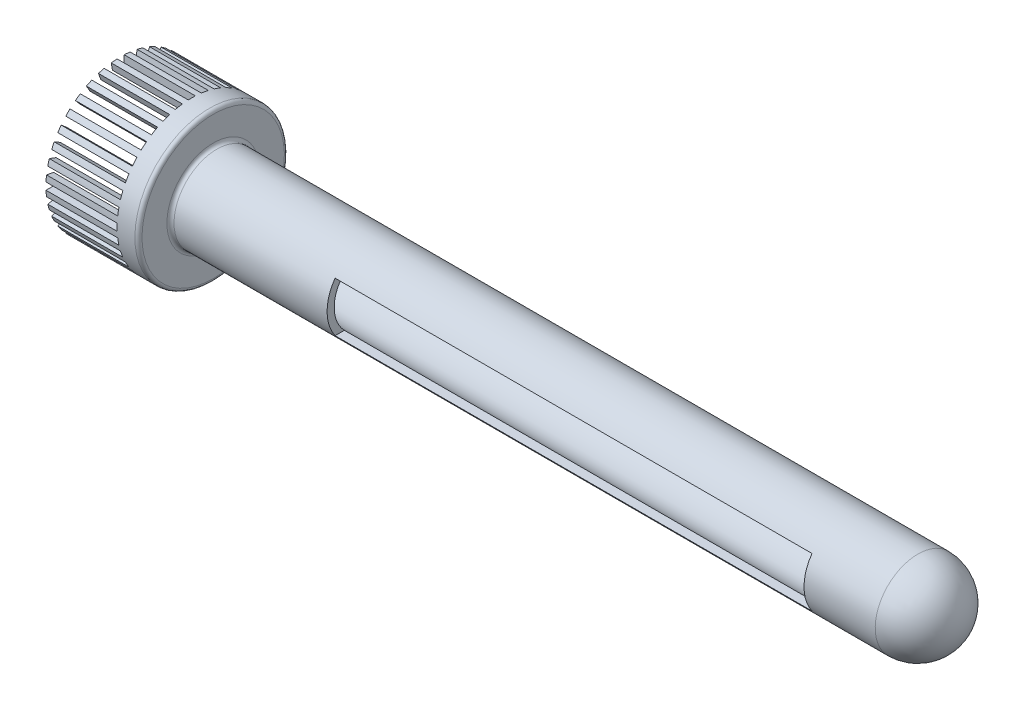
SolidWorks part; units mm, degrees
ref_plane "前视基准面" through (0, 0, 0) normal (0, 0, 1) x (1, 0, 0)
ref_plane "上视基准面" through (0, 0, 0) normal (0, 1, 0) x (1, 0, 0)
ref_plane "右视基准面" through (0, 0, 0) normal (1, 0, 0) x (0, 0, -1)
sketch "草图1" plane through (0, 0, 0) normal (0, 0, 1) x (1, 0, 0)
  line L5 (-49.9652, 5) -> (50.0348, 5)
  line L12 (-49.9652, 9.5) -> (-49.9652, 5)
  line L13 (-49.9652, 9.5) -> (-61.9652, 9.5)
  line L15 (-48.9652, 10.5) -> (-61.9652, 10.5)
  line L16 (-48.9652, 10.5) -> (-48.9652, 6)
  line L17 (-48.9652, 6) -> (50.0381, 6)
  line L18 (-61.9652, 10.5) -> (-61.9652, 9.5)
  line L19 (0, 0) -> (20.4046, 0) construction
  line L20 (55.9999, 0) -> (54.9999, 0)
  arc A1 (54.9999, 0) -> (50.0348, 5) centre (49.9998, 0) ccw
  arc A4 (55.9999, 0) -> (50.0381, 6) centre (49.9998, 0) ccw
  point P0 (0, 0)
  dimension "D3" = 100
  dimension "D1" = 5
  dimension "D4" = 1
  dimension "D5" = 4.5
  dimension "D6" = 12
  dimension "D7" = 5.0001
revolve "旋转1" add sketch "草图1" angle 360 about L19
sketch "草图3" plane through (0, 0, 0) normal (0, 0, 1) x (1, 0, 0)
  line L0 (-26.9652, -3.5) -> (40.0348, -3.5)
  line L1 (-26.9652, 3.5) -> (40.0348, 3.5)
  line L2 (-26.9652, 3.5) -> (-26.9652, -3.5)
  line L4 (40.0348, 3.5) -> (40.0348, -3.5)
  point P0 (6.5348, 1.75)
  point P11 (6.5348, -1.75)
  dimension "D1" = 23
extrude "切除-拉伸11" cut sketch "草图3" against normal through all both and the other way through all
sketch "草图5" plane through (-61.9652, 0, 0) normal (-1, 0, 0) x (0, 0, 1)
  line L0 (0, 0) -> (9.5, 0) construction
  line L1 (-11, 0.5) -> (-9, 0.5)
  line L2 (-11, 0.5) -> (-11, -0.5)
  line L3 (-11, -0.5) -> (-9, -0.5)
  line L4 (-9, 0.5) -> (-9, -0.5)
  line L5 (-11, 0.5) -> (-9, -0.5) construction
  line L6 (-11, -0.5) -> (-9, 0.5) construction
  line L7 (-10.5, 0) -> (-9.5, 0)
  circle A2 centre (0, 0) radius 10.5 construction
  circle A3 centre (0, 0) radius 9.5 construction
  point P0 (-10, 0)
  point P17 (-10, 0)
  dimension "D1" = 2
  dimension "D2" = 1
extrude "切除-拉伸12" cut sketch "草图5" against normal blind 10 contours L1 L4 L3 L2
pattern_circular "阵列(圆周)1" count 36 over 360 about axis through (0, 0, 0) along (1, 0, 0) of "切除-拉伸12"
fillet "圆角1" radius 0.5 1 edges at (-49.9652, -5, 0)
fillet "圆角2" radius 0.5 1 edges at (-49.9652, -9.5, 0)
fillet "圆角3" radius 0.5 1 edges at (-48.9652, -10.5, 0)
fillet "圆角4" radius 0.5 1 edges at (-48.9652, -6, 0)
